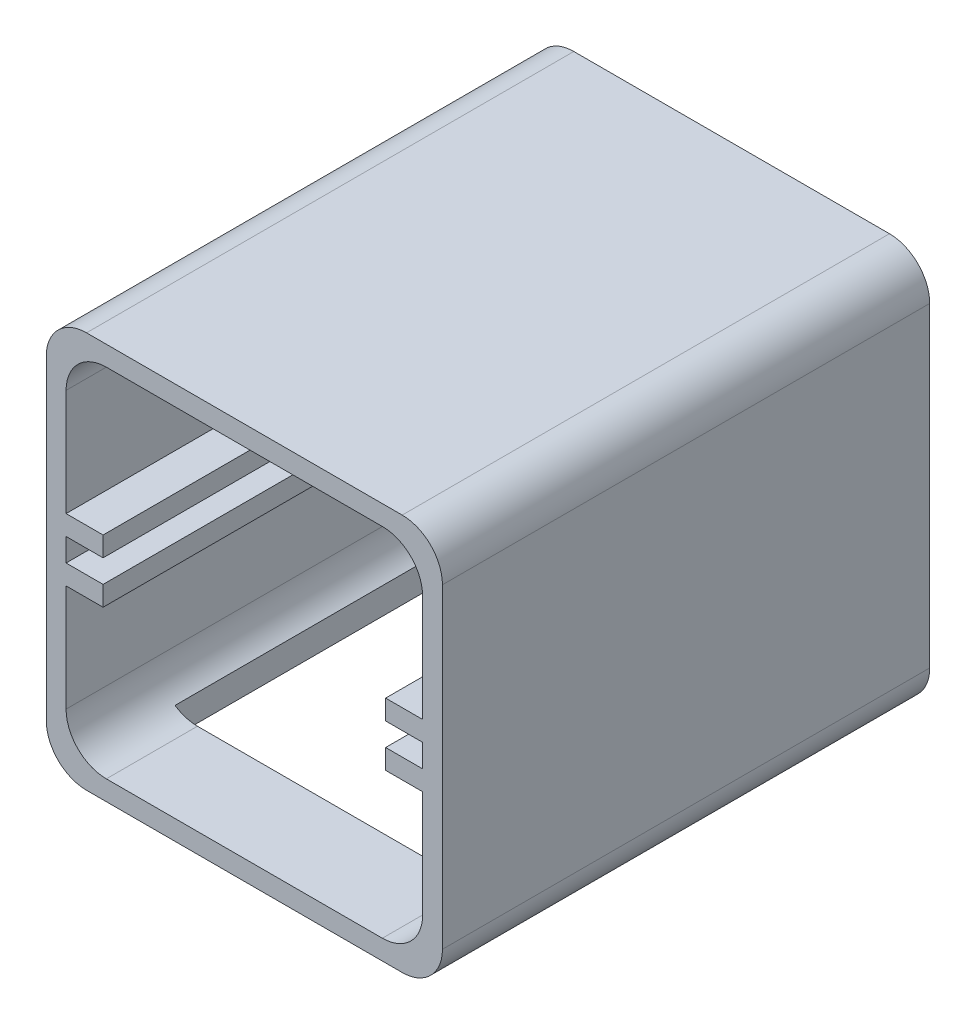
SolidWorks part; units mm, degrees
ref_plane "Front Plane" through (0, 0, 0) normal (0, 0, 1) x (1, 0, 0)
ref_plane "Top Plane" through (0, 0, 0) normal (0, 1, 0) x (1, 0, 0)
ref_plane "Right Plane" through (0, 0, 0) normal (1, 0, 0) x (0, 0, -1)
sketch "Sketch1" plane through (0, 0, 0) normal (0, 0, 1) x (1, 0, 0)
  line L1 (0, 0) -> (100, 0)
  line L2 (0, 0) -> (0, 100)
  line L3 (0, 100) -> (100, 100)
  line L4 (100, 0) -> (100, 100)
  line L5 (3, 3) -> (97, 3)
  line L6 (3, 3) -> (3, 97)
  line L7 (3, 97) -> (97, 97)
  line L8 (97, 3) -> (97, 97)
  dimension "D1" = 100
  dimension "D2" = 100
  dimension "D3" = 3
  dimension "D4" = 3
  dimension "D5" = 3
  dimension "D6" = 3
extrude "Boss-Extrude1" add sketch "Sketch1" along normal blind 250 contours L2 L1 L4 L3
sketch "Sketch2" plane through (0, 0, 0) normal (0, 0, -1) x (-1, 0, 0)
  line L1 (-95, 5) -> (-5, 5)
  line L2 (-95, 5) -> (-95, 95)
  line L3 (-95, 95) -> (-5, 95)
  line L4 (0, 100) -> (-100, 100)
  line L5 (-100, 100) -> (-100, 0)
  line L6 (-100, 0) -> (0, 0)
  line L7 (0, 0) -> (0, 100)
  line L8 (0, 100) -> (-100, 100)
  line L9 (-100, 100) -> (-100, 0)
  line L10 (-100, 0) -> (0, 0)
  line L11 (0, 0) -> (0, 100)
  line L12 (-5, 5) -> (-5, 95)
  dimension "D2" = 5
  dimension "D3" = 5
  dimension "D4" = 5
  dimension "D5" = 5
  dimension "D1" = 0
extrude "Cut-Extrude1" cut sketch "Sketch2" against normal through all contours L2 L1 L12 L3
fillet "Fillet1" radius 10.16 4 edges at (0, 100, 125) (0, 0, 125) (100, 100, 125) (100, 0, 125)
sketch "Sketch3" plane through (0, 0, 0) normal (0, 0, -1) x (-1, 0, 0)
  line L0 (-95, 50) -> (-5, 50) construction
  line L1 (-95, 5) -> (-95, 95) construction
  line L2 (-5, 5) -> (-5, 95) construction
  line L3 (-95, 57.9) -> (-85.6588, 57.9)
  line L4 (-85.6588, 57.9) -> (-85.6588, 52.9)
  line L5 (-85.6588, 52.9) -> (-95, 52.9)
  line L6 (-95, 52.9) -> (-95, 50)
  line L7 (-95, 50) -> (-95, 47.1)
  line L8 (-95, 47.1) -> (-85.6588, 47.1)
  line L9 (-85.6588, 47.1) -> (-85.6588, 42.1)
  line L10 (-85.6588, 42.1) -> (-95, 42.1)
  line L11 (-95, 42.1) -> (-95, 47.1)
  line L12 (-95, 57.9) -> (-95, 52.9)
  line L13 (-50, 67.1729) -> (-50, 35.9029) construction
  line L14 (-5, 42.1) -> (-5, 47.1)
  line L15 (-14.3412, 42.1) -> (-5, 42.1)
  line L16 (-14.3412, 47.1) -> (-14.3412, 42.1)
  line L17 (-5, 47.1) -> (-14.3412, 47.1)
  line L18 (-5, 57.9) -> (-5, 52.9)
  line L19 (-5, 57.9) -> (-14.3412, 57.9)
  line L20 (-14.3412, 57.9) -> (-14.3412, 52.9)
  line L21 (-14.3412, 52.9) -> (-5, 52.9)
  point P8 (-50, 50)
  dimension "D1" = 9.3412
  dimension "D2" = 5
  dimension "D3" = 5
  dimension "D4" = 5.8
  dimension "D5" = 2.9
extrude "Boss-Extrude2" add sketch "Sketch3" against normal through all contours L5 L4 L3 L12 | L8 L9 L10 L11 | L18 L21 L20 L19 | L14 L17 L16 L15
sketch "Sketch4" plane through (0, 100, 0) normal (0, 1, 0) x (1, 0, 0)
  line L0 (100, 0) -> (100, -250) construction
  line L1 (0, 0) -> (100, 0)
  line L2 (0, 0) -> (0, -125)
  line L3 (0, -125) -> (100, -125)
  line L4 (100, 0) -> (100, -125)
  dimension "D1" = 125
extrude "Cut-Extrude2" cut sketch "Sketch4" against normal through all
sketch "Sketch6" plane through (0, 0, 0) normal (0, -1, 0) x (1, 0, 0)
  line L0 (10.16, 125) -> (89.84, 125) construction
  line L1 (9.5, 225) -> (90.5, 225)
  line L2 (9.5, 225) -> (9.5, 125)
  line L3 (9.5, 125) -> (90.5, 125)
  line L4 (90.5, 225) -> (90.5, 125)
  point P6 (50, 125)
  point P7 (50, 125)
  dimension "D1" = 100
  dimension "D2" = 81
extrude "Cut-Extrude4" cut sketch "Sketch6" against normal up to surface (5 mm away) up to face at (50, 5, 187.5)
fillet "Fillet3" radius 10.16 4 edges at (5, 95, 187.5) (5, 5, 187.5) (95, 95, 187.5) (95, 5, 187.5)
sketch "Sketch7" plane through (0, 0, 125) normal (0, 0, -1) x (-1, 0, 0)
  line L0 (-95, 57.9) -> (-95, 84.84) construction
  line L1 (-95, 96) -> (-5, 96)
  line L2 (-95, 96) -> (-95, 57.9)
  line L3 (-95, 57.9) -> (-86.703, 57.9)
  line L4 (-5, 96) -> (-5, 57.9)
  line L5 (-10.16, 100) -> (-89.84, 100) construction
  line L6 (-86.703, 92.952) -> (-13.297, 92.952)
  line L7 (-86.703, 92.952) -> (-86.703, 57.9)
  line L9 (-13.297, 92.952) -> (-13.297, 57.9)
  line L11 (-13.297, 57.9) -> (-5, 57.9)
  point P13 (-50, 100)
  point P14 (-50, 92.952)
  dimension "D1" = 38.1
  dimension "D2" = 73.406
  dimension "D3" = 35.052
extrude "Boss-Extrude3" add sketch "Sketch7" against normal blind 30.48
sketch "Sketch9" plane through (0, 92.952, 0) normal (0, -1, 0) x (1, 0, 0)
  line L0 (86.703, 155.48) -> (86.703, 125) construction
  line L1 (13.297, 155.48) -> (86.703, 155.48)
  line L2 (13.297, 155.48) -> (13.297, 149.23)
  line L3 (13.297, 149.23) -> (86.703, 149.23)
  line L4 (86.703, 155.48) -> (86.703, 149.23)
  dimension "D1" = 6.25
extrude "Boss-Extrude5" add sketch "Sketch9" along normal up to surface (35.052 mm away) up to face at (10.8794, 57.9, 176.8267)
sketch "Sketch10" plane through (0, 0, 250) normal (0, 0, 1) x (1, 0, 0)
  line L4 (89.84, 100) -> (10.16, 100)
  line L5 (0, 89.84) -> (0, 10.16)
  line L6 (10.16, 0) -> (89.84, 0)
  line L7 (100, 10.16) -> (100, 89.84)
  line L8 (89.84, 100) -> (10.16, 100)
  line L9 (0, 89.84) -> (0, 10.16)
  line L10 (10.16, 0) -> (89.84, 0)
  line L11 (100, 10.16) -> (100, 89.84)
  arc A4 (10.16, 100) -> (0, 89.84) centre (10.16, 89.84) ccw
  arc A5 (0, 10.16) -> (10.16, 0) centre (10.16, 10.16) ccw
  arc A6 (89.84, 0) -> (100, 10.16) centre (89.84, 10.16) ccw
  arc A7 (100, 89.84) -> (89.84, 100) centre (89.84, 89.84) ccw
  arc A8 (10.16, 100) -> (0, 89.84) centre (10.16, 89.84) ccw
  arc A9 (0, 10.16) -> (10.16, 0) centre (10.16, 10.16) ccw
  arc A10 (89.84, 0) -> (100, 10.16) centre (89.84, 10.16) ccw
  arc A11 (100, 89.84) -> (89.84, 100) centre (89.84, 89.84) ccw
  dimension "D1" = 0
extrude "Cut-Extrude5" cut sketch "Sketch10" against normal blind 2
